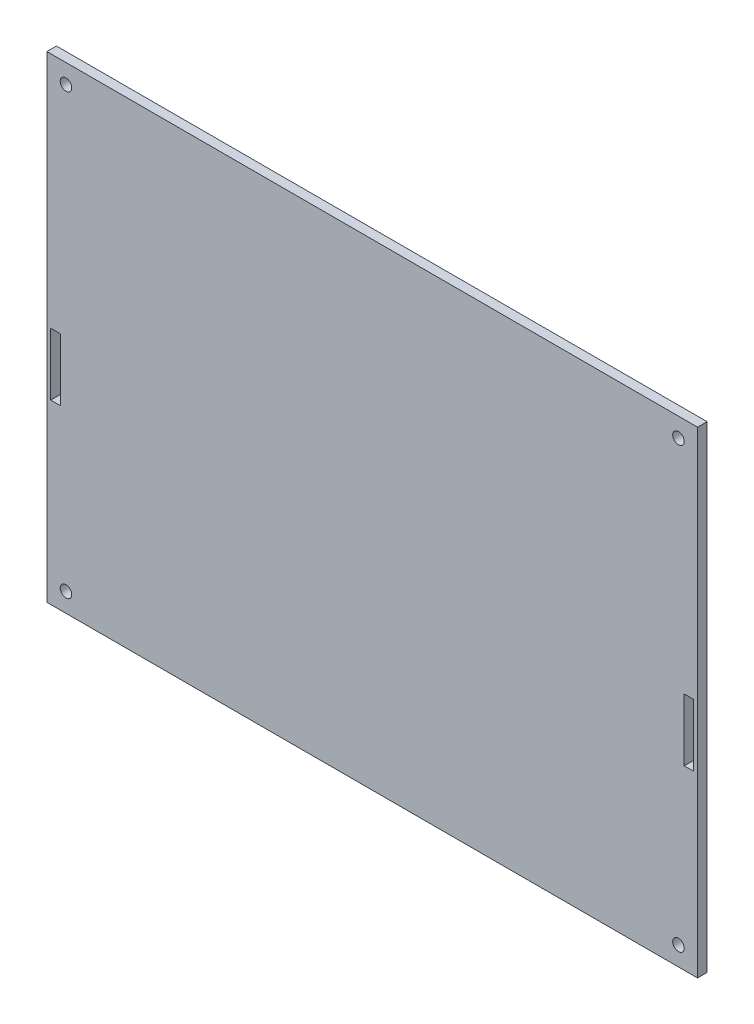
SolidWorks part; units mm, degrees
ref_plane "Front Plane" through (0, 0, 0) normal (0, 0, 1) x (1, 0, 0)
ref_plane "Top Plane" through (0, 0, 0) normal (0, 1, 0) x (1, 0, 0)
ref_plane "Right Plane" through (0, 0, 0) normal (1, 0, 0) x (0, 0, -1)
sketch "Sketch1" plane through (0, 0, 0) normal (0, 0, 1) x (1, 0, 0)
  line L0 (160.5, -240) -> (160.5, -79.3542) construction
  line L1 (331, 10) -> (-10, 10)
  line L2 (331, 10) -> (331, -240)
  line L3 (331, -240) -> (-10, -240)
  line L4 (-10, 10) -> (-10, -240)
  line L5 (-3, -114.6) -> (-8, -114.6)
  line L6 (-3, -114.6) -> (-3, -147.2059)
  line L7 (-3, -147.2059) -> (-8, -147.2059)
  line L8 (-8, -114.6) -> (-8, -147.2059)
  line L9 (329, -114.6) -> (329, -147.2059)
  line L10 (324, -147.2059) -> (329, -147.2059)
  line L11 (324, -114.6) -> (324, -147.2059)
  line L12 (324, -114.6) -> (329, -114.6)
  circle A2 centre (0, -230) radius 3.025
  circle A4 centre (0, 0) radius 3.025
  circle A6 centre (321, 0) radius 3.025
  circle A8 centre (321, -230) radius 3.025
extrude "Boss-Extrude1" add sketch "Sketch1" along normal blind 5
